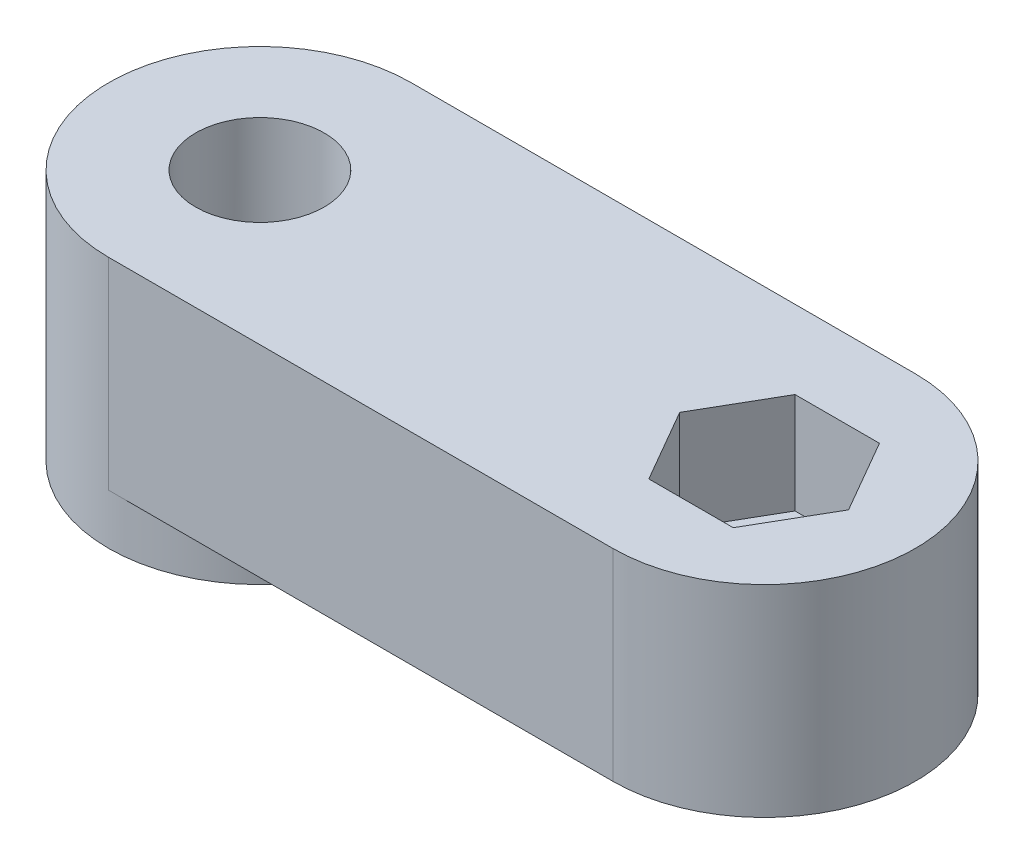
SolidWorks part; units mm, degrees
ref_plane "前视基准面" through (0, 0, 0) normal (0, 0, 1) x (1, 0, 0)
ref_plane "上视基准面" through (0, 0, 0) normal (0, 1, 0) x (1, 0, 0)
ref_plane "右视基准面" through (0, 0, 0) normal (1, 0, 0) x (0, 0, -1)
sketch "草图1" plane through (0, 0, 0) normal (0, 1, 0) x (1, 0, 0)
  line L0 (0, 0) -> (20, 0) construction
  line L1 (0, 6) -> (20, 6)
  line L2 (0, -6) -> (20, -6)
  arc A0 (0, 6) -> (0, -6) centre (0, 0) ccw
  arc A1 (20, -6) -> (20, 6) centre (20, 0) ccw
  point P2 (10, 0)
  dimension "D1" = 12
  dimension "D2" = 20
extrude "凸台-拉伸1" add sketch "草图1" along normal blind 10
sketch "草图3" plane through (0, 0, 0) normal (0, 0, 1) x (1, 0, 0)
  line L0 (0, 10) -> (0, 0) construction
  line L1 (0, 10) -> (-2.55, 10)
  line L2 (0, 10) -> (-6, 10) construction
  line L3 (-2.55, 10) -> (-2.55, 5)
  line L4 (-2.55, 5) -> (-2.1, 5)
  line L5 (-2.1, 5) -> (-2.1, 2)
  line L6 (-2.1, 2) -> (-2.55, 2)
  line L7 (-2.55, 2) -> (-2.55, 0)
  line L8 (-6, 0) -> (0, 0) construction
  line L9 (-2.55, 0) -> (0, 0)
  line L10 (0, 10) -> (0, 0)
  dimension "D1" = 5.1
  dimension "D2" = 5
  dimension "D3" = 3
  dimension "D4" = 4.2
revolve "切除-旋转2" cut sketch "草图3" angle 360 about L0
sketch "草图4" plane through (0, 0, 0) normal (0, 0, 1) x (1, 0, 0)
  line L0 (20, 10) -> (20, 0) construction
  line L1 (20, 10) -> (17.5, 10)
  line L2 (0, 10) -> (20, 10) construction
  line L3 (17.5, 10) -> (17.5, 5)
  line L4 (17.5, 5) -> (17.925, 5)
  line L5 (17.925, 5) -> (17.925, 0)
  line L6 (0, 0) -> (20, 0) construction
  line L7 (17.925, 0) -> (20, 0)
  line L8 (20, 10) -> (20, 0)
  dimension "D1" = 5
  dimension "D2" = 5
  dimension "D3" = 4.15
revolve "切除-旋转3" cut sketch "草图4" angle 360 about L0
sketch "草图5" plane through (0, 0, 0) normal (0, -1, 0) x (1, 0, 0)
  line L0 (0, 6) -> (20, 6) construction
  line L1 (-4.2147, 0) -> (-2.1073, -3.65)
  line L2 (-2.1073, -3.65) -> (2.1073, -3.65)
  line L3 (2.1073, -3.65) -> (4.2147, 0)
  line L4 (4.2147, 0) -> (2.1073, 3.65)
  line L5 (2.1073, 3.65) -> (-2.1073, 3.65)
  line L6 (-2.1073, 3.65) -> (-4.2147, 0)
  circle A0 centre (0, 0) radius 3.65 construction
  dimension "D1" = 7.3
extrude "切除-拉伸1" cut sketch "草图5" against normal blind 5
sketch "草图6" plane through (0, 0, 0) normal (0, -1, 0) x (1, 0, 0)
  circle A0 centre (0, 0) radius 27.318
  circle A1 centre (0, 0) radius 6
  arc A2 (0, 6) -> (0, -6) centre (0, 0) ccw construction
extrude "切除-拉伸2" cut sketch "草图6" against normal blind 2
sketch "草图7" plane through (0, 10, 0) normal (0, 1, 0) x (1, 0, 0)
  line L0 (0, -6) -> (20, -6) construction
  line L1 (18.3257, 2.9) -> (16.6514, 0)
  line L2 (16.6514, 0) -> (18.3257, -2.9)
  line L3 (18.3257, -2.9) -> (21.6743, -2.9)
  line L4 (21.6743, -2.9) -> (23.3486, 0)
  line L5 (23.3486, 0) -> (21.6743, 2.9)
  line L6 (21.6743, 2.9) -> (18.3257, 2.9)
  circle A0 centre (20, 0) radius 2.9 construction
  dimension "D1" = 5.8
extrude "切除-拉伸3" cut sketch "草图7" against normal blind 4
